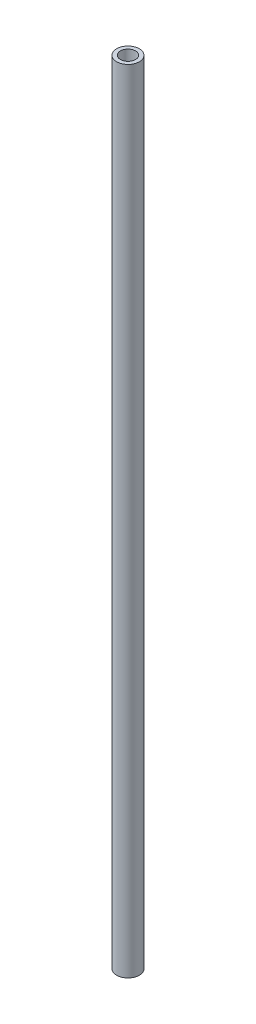
SolidWorks part; units mm, degrees
material "1060-H12 棒材(SS)"
ref_plane "前视基准面" through (0, 0, 0) normal (0, 0, 1) x (1, 0, 0)
ref_plane "上视基准面" through (0, 0, 0) normal (0, 1, 0) x (1, 0, 0)
ref_plane "右视基准面" through (0, 0, 0) normal (1, 0, 0) x (0, 0, -1)
sketch "草图1" plane through (0, 0, 0) normal (0, 1, 0) x (1, 0, 0)
  circle A0 centre (0, 0) radius 4
  circle A1 centre (0, 0) radius 6
  dimension "D1" = 8
  dimension "D2" = 12
extrude "凸台-拉伸1" add sketch "草图1" along normal blind 420
